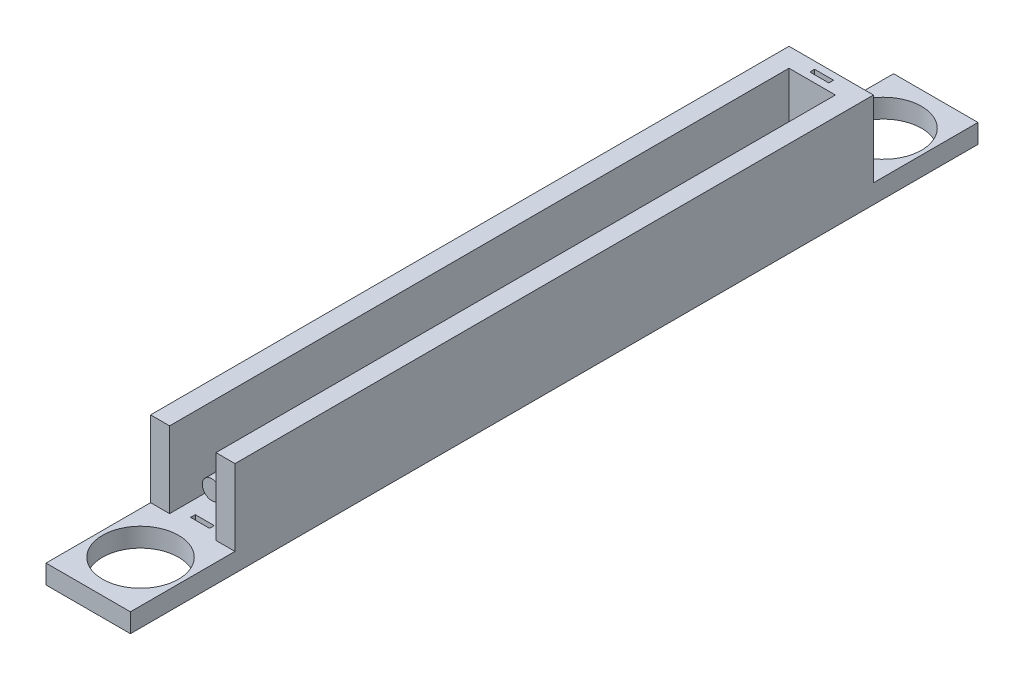
SolidWorks part; units mm, degrees
material "PP Kopolimer"
ref_plane "Front Plane" through (0, 0, 0) normal (0, 0, 1) x (1, 0, 0)
ref_plane "Top Plane" through (0, 0, 0) normal (0, 1, 0) x (1, 0, 0)
ref_plane "Right Plane" through (0, 0, 0) normal (1, 0, 0) x (0, 0, -1)
sketch "Szkic1" plane through (0, 0, 0) normal (0, 1, 0) x (1, 0, 0)
  line L1 (-2.22, -16.79) -> (2.22, -16.79)
  line L2 (-2.22, -16.79) -> (-2.22, 16.79)
  line L3 (-2.22, 16.79) -> (2.22, 16.79)
  line L4 (2.22, -16.79) -> (2.22, 16.79)
  line L5 (-2.22, -16.79) -> (2.22, 16.79) construction
  line L6 (-2.22, 16.79) -> (2.22, -16.79) construction
  point P0 (0, 0)
  dimension "D1" = 33.58
  dimension "D2" = 4.44
extrude "Dodanie-wyciągnięcie1" add sketch "Szkic1" along normal blind 1
sketch "Szkic2" plane through (0, 1, 0) normal (0, 1, 0) x (1, 0, 0)
  line L0 (-2.22, -16.79) -> (2.22, -16.79) construction
  line L2 (-2.22, 16.79) -> (-2.22, -16.79)
  line L3 (-2.22, -16.79) -> (-1.22, -16.79)
  line L4 (-1.22, 15.79) -> (-1.22, -16.79)
  line L6 (2.22, -16.79) -> (1.22, -16.79)
  line L7 (2.22, -16.79) -> (2.22, 16.79)
  line L9 (1.22, -16.79) -> (1.22, 15.79)
  line L10 (-2.22, 16.79) -> (2.22, 16.79)
  line L13 (-1.22, 15.79) -> (1.22, 15.79)
extrude "Dodanie-wyciągnięcie2" add sketch "Szkic2" along normal blind 4
sketch "Szkic3" plane through (0, 0, -15.79) normal (0, 0, 1) x (1, 0, 0)
  line L0 (0, 1) -> (0, 2.2) construction
  line L1 (-1.22, 1) -> (1.22, 1) construction
  circle A0 centre (0, 2.2) radius 0.5
extrude "Dodanie-wyciągnięcie3" add sketch "Szkic3" along normal blind 31.58
sketch "Szkic4" plane through (0, 1, 0) normal (0, 1, 0) x (1, 0, 0)
  line L0 (0, -16.79) -> (0, -15.7771) construction
  line L1 (-1.22, -16.79) -> (1.22, -16.79) construction
  line L3 (-0.5, -16.1585) -> (0.5, -16.1585)
  line L4 (-0.5, -16.1585) -> (-0.5, -16.4085)
  line L5 (-0.5, -16.4085) -> (0.5, -16.4085)
  line L6 (0.5, -16.1585) -> (0.5, -16.4085)
  line L7 (-0.5, -16.1585) -> (0.5, -16.4085) construction
  line L8 (-0.5, -16.4085) -> (0.5, -16.1585) construction
  point P5 (0, -16.2835)
extrude "Wytnij-wyciągnięcie1" cut sketch "Szkic4" against normal blind 31.58
sketch "Szkic5" plane through (0, 5, 0) normal (0, 1, 0) x (1, 0, 0)
  line L0 (0, 16.79) -> (0, 15.79) construction
  line L1 (2.22, 16.79) -> (-2.22, 16.79) construction
  line L2 (-1.22, 15.79) -> (1.22, 15.79) construction
  line L4 (-0.5, 16.415) -> (0.5, 16.415)
  line L5 (-0.5, 16.415) -> (-0.5, 16.165)
  line L6 (-0.5, 16.165) -> (0.5, 16.165)
  line L7 (0.5, 16.415) -> (0.5, 16.165)
  line L8 (-0.5, 16.415) -> (0.5, 16.165) construction
  line L9 (-0.5, 16.165) -> (0.5, 16.415) construction
  point P6 (0, 16.29)
extrude "Wytnij-wyciągnięcie2" cut sketch "Szkic5" against normal blind 1
sketch "Szkic6" plane through (0, 0, 16.79) normal (0, 0, 1) x (1, 0, 0)
  line L0 (-2.22, 5) -> (-2.22, 0) construction
  line L1 (2.22, 0) -> (-2.22, 0)
  line L2 (2.22, 0) -> (2.22, 1)
  line L3 (2.22, 1) -> (-2.22, 1)
  line L4 (-2.22, 0) -> (-2.22, 1)
extrude "Dodanie-wyciągnięcie5" add sketch "Szkic6" along normal blind 5.5
sketch "Szkic8" plane through (0, 1, 0) normal (0, 1, 0) x (1, 0, 0)
  line L0 (0, -22.29) -> (0, -16.7883) construction
  line L1 (2.22, -22.29) -> (-2.22, -22.29) construction
  circle A0 centre (0, -19.5392) radius 2
extrude "Wytnij-wyciągnięcie3" cut sketch "Szkic8" against normal blind 5.5
sketch "Szkic9" plane through (0, 0, -16.79) normal (0, 0, -1) x (-1, 0, 0)
  line L0 (2.22, 5) -> (2.22, 0) construction
  line L1 (-2.22, 0) -> (2.22, 0)
  line L2 (-2.22, 0) -> (-2.22, 1)
  line L3 (-2.22, 1) -> (2.22, 1)
  line L4 (2.22, 0) -> (2.22, 1)
extrude "Dodanie-wyciągnięcie6" add sketch "Szkic9" along normal blind 5.5
sketch "Szkic11" plane through (0, 1, 0) normal (0, 1, 0) x (1, 0, 0)
  line L0 (0, 22.29) -> (0, 16.79) construction
  line L1 (-2.22, 22.29) -> (2.22, 22.29) construction
  line L2 (-2.22, 16.79) -> (2.22, 16.79) construction
  circle A0 centre (0, 19.54) radius 2
extrude "Wytnij-wyciągnięcie4" cut sketch "Szkic11" against normal blind 5.5
